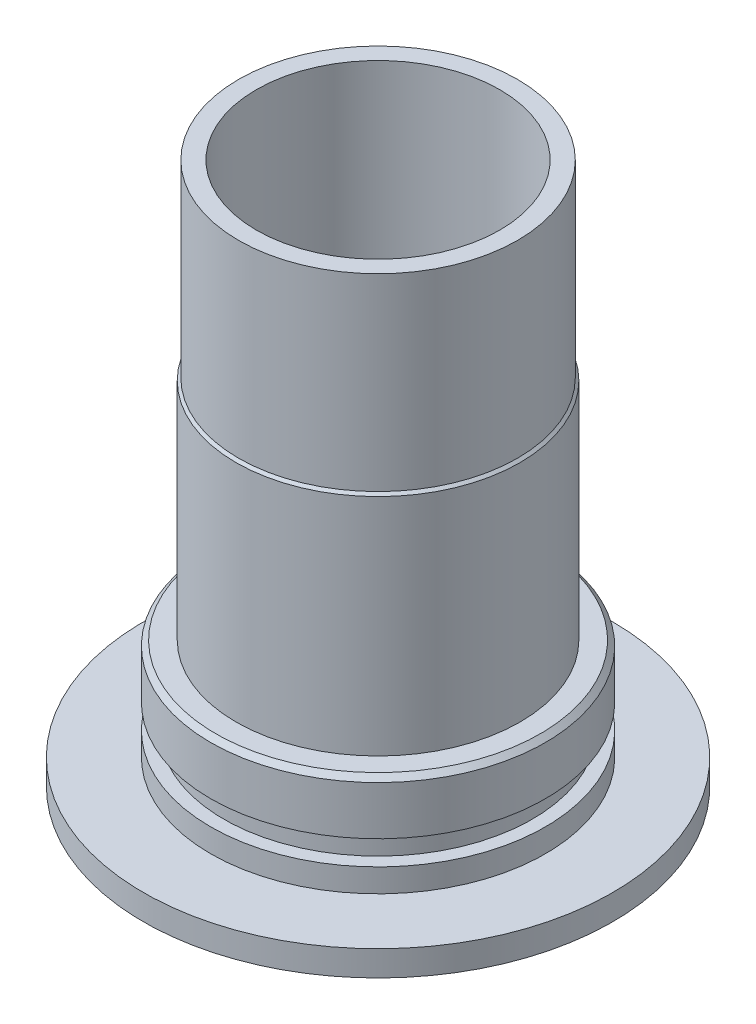
SolidWorks part; units mm, degrees
ref_plane "Front Plane" through (0, 0, 0) normal (0, 0, 1) x (1, 0, 0)
ref_plane "Top Plane" through (0, 0, 0) normal (0, 1, 0) x (1, 0, 0)
ref_plane "Right Plane" through (0, 0, 0) normal (1, 0, 0) x (0, 0, -1)
sketch "Sketch1" plane through (0, 0, 0) normal (0, 0, 1) x (1, 0, 0)
  line L0 (0, 0) -> (0, 119.4102) construction
  line L1 (24, 154) -> (27.5, 154)
  line L2 (27.5, 154) -> (27.5, 69.8)
  line L3 (27.5, 69.8) -> (28, 69.3)
  line L4 (28, 69.3) -> (28, 25)
  line L5 (28, 25) -> (32, 25)
  line L6 (32, 25) -> (33, 24)
  line L7 (33, 24) -> (33, 14.4)
  line L8 (33, 14.4) -> (30.4, 14.4)
  line L9 (30.4, 14.4) -> (30.4, 9.6)
  line L10 (30.4, 9.6) -> (33, 9.6)
  line L11 (33, 9.6) -> (33, 5)
  line L12 (33, 5) -> (46.25, 5)
  line L13 (46.25, 5) -> (46.25, 0)
  line L14 (46.25, 0) -> (26.775, 0)
  line L15 (25.925, 0) -> (26.35, 0.5)
  line L16 (26.35, 0.5) -> (26.775, 0)
  line L18 (24, 0) -> (24, 154)
  line L19 (0, 0) -> (24, 0) construction
  line L20 (26.35, 0.5) -> (26.35, 0) construction
  line L21 (26.775, 0) -> (25.925, 0) construction
  line L23 (25.925, 0) -> (24, 0)
  dimension "D1" = 92.5
  dimension "D2" = 48
  dimension "D3" = 55
  dimension "D4" = 56
  dimension "D5" = 5
  dimension "D6" = 2.6
  dimension "D7" = 4.8
  dimension "D8" = 4.6
  dimension "D9" = 66
  dimension "D10" = 10.6
  dimension "D11" = 1
  dimension "D12" = 135
  dimension "D13" = 44.3
  dimension "D14" = 154
  dimension "D15" = 52.7
  dimension "D16" = 0.5
  dimension "D17" = 0.85
revolve "Revolve1" add sketch "Sketch1" angle 360 about L0
sketch "Sketch2" plane through (0, 154, 0) normal (0, 1, 0) x (1, 0, 0)
  circle A0 centre (0, 0) radius 37.5
  dimension "D1" = 75
extrude "Cut-Extrude1" cut sketch "Sketch2" against normal blind 47
